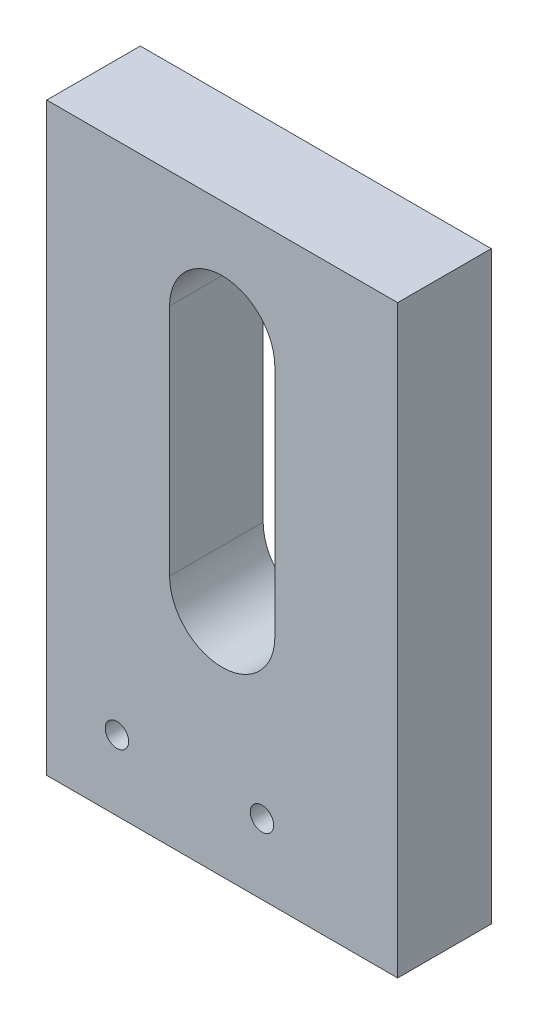
SolidWorks part; units mm, degrees
ref_plane "Front Plane" through (0, 0, 0) normal (0, 0, 1) x (1, 0, 0)
ref_plane "Top Plane" through (0, 0, 0) normal (0, 1, 0) x (1, 0, 0)
ref_plane "Right Plane" through (0, 0, 0) normal (1, 0, 0) x (0, 0, -1)
sketch "Sketch1" plane through (0, 0, 0) normal (0, 0, 1) x (1, 0, 0)
  line L0 (7.5, 20) -> (7.5, 10) construction
  line L1 (0, 0) -> (15, 0)
  line L2 (0, 0) -> (0, 25)
  line L3 (0, 25) -> (15, 25)
  line L4 (15, 0) -> (15, 25)
  line L5 (9.75, 20) -> (9.75, 10)
  line L6 (5.25, 20) -> (5.25, 10)
  arc A0 (9.75, 20) -> (5.25, 20) centre (7.5, 20) ccw
  arc A1 (5.25, 10) -> (9.75, 10) centre (7.5, 10) ccw
  circle A4 centre (3, 3) radius 0.5
  circle A5 centre (9.2, 3) radius 0.5
  point P7 (7.5, 15)
  point P16 (0, 0)
  point P17 (0, 0)
  dimension "D4" = 5
  dimension "D5" = 2.25
  dimension "D10" = 1
  dimension "D1" = 15
  dimension "D2" = 25
  dimension "D3" = 10
  dimension "D6" = 7.5
  dimension "D7" = 6.2
  dimension "D8" = 3
  dimension "D9" = 3
extrude "Boss-Extrude1" add sketch "Sketch1" along normal blind 4
